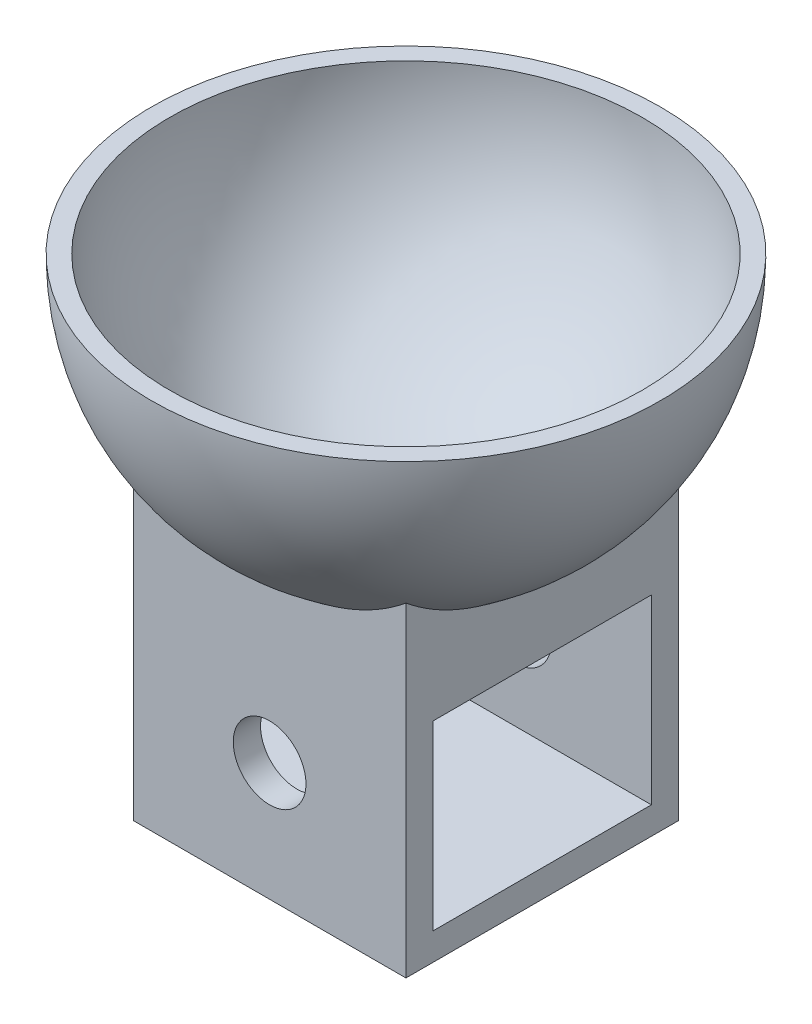
SolidWorks part; units mm, degrees
ref_plane "Front Plane" through (0, 0, 0) normal (0, 0, 1) x (1, 0, 0)
ref_plane "Top Plane" through (0, 0, 0) normal (0, 1, 0) x (1, 0, 0)
ref_plane "Right Plane" through (0, 0, 0) normal (1, 0, 0) x (0, 0, -1)
sketch "Sketch1" plane through (0, 0, 0) normal (0, 1, 0) x (1, 0, 0)
  line L1 (-15, -15) -> (15, -15)
  line L2 (-15, -15) -> (-15, 15)
  line L3 (-15, 15) -> (15, 15)
  line L4 (15, -15) -> (15, 15)
  line L5 (-15, -15) -> (15, 15) construction
  line L6 (-15, 15) -> (15, -15) construction
  point P0 (0, 0)
  dimension "D1" = 30
  dimension "D2" = 30
extrude "Boss-Extrude1" add sketch "Sketch1" along normal blind 26
shell "Shell1" thickness 3
sketch "Sketch3" plane through (0, 0, 15) normal (0, 0, 1) x (1, 0, 0)
  line L0 (-15, 0) -> (15, 26) construction
  line L2 (-15, 26) -> (15, 0) construction
  circle A0 centre (0, 13) radius 4
  point P6 (0, 13)
  dimension "D1" = 8
extrude "Cut-Extrude1" cut sketch "Sketch3" against normal through all
sketch "Sketch5" plane through (0, 0, 0) normal (0, 0, 1) x (1, 0, 0)
  line L0 (0, 26) -> (0, 54) construction
  line L1 (-15, 26) -> (15, 26) construction
  line L2 (-28, 54) -> (-26, 54)
  line L3 (0, 28) -> (0, 26)
  arc A0 (0, 26) -> (-28, 54) centre (0, 54) cw
  arc A1 (0, 28) -> (-26, 54) centre (0, 54) cw
  dimension "D1" = 2
  dimension "D2" = 28
revolve "Revolve1" add sketch "Sketch5" angle 360 about L0
sketch "Sketch6" plane through (0, 26, 0) normal (0, 1, 0) x (1, 0, 0)
  line L0 (-15, 15) -> (-15, -15)
  line L1 (-15, -15) -> (15, -15)
  line L2 (15, -15) -> (15, 15)
  line L3 (15, 15) -> (-15, 15)
extrude "Boss-Extrude2" add sketch "Sketch6" along normal up to next
